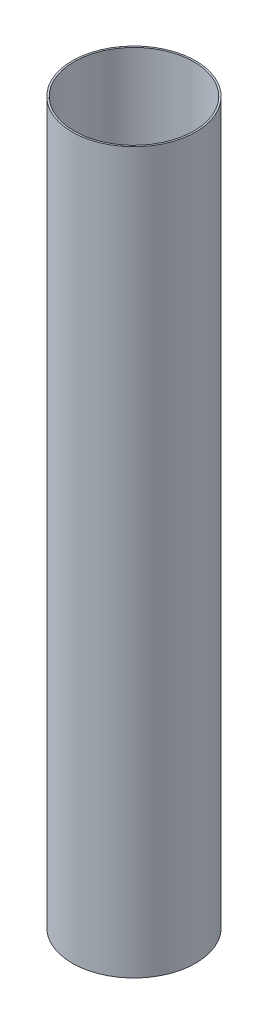
SolidWorks part; units mm, degrees
ref_plane "Front Plane" through (0, 0, 0) normal (0, 0, 1) x (1, 0, 0)
ref_plane "Top Plane" through (0, 0, 0) normal (0, 1, 0) x (1, 0, 0)
ref_plane "Right Plane" through (0, 0, 0) normal (1, 0, 0) x (0, 0, -1)
sketch "Sketch1" plane through (0, 0, 0) normal (0, 1, 0) x (1, 0, 0)
  circle A0 centre (0, 0) radius 76.2
  circle A1 centre (0, 0) radius 78.359
  dimension "D1" = 156.718
  dimension "D2" = 152.4
extrude "Boss-Extrude1" add sketch "Sketch1" along normal blind 914.4
